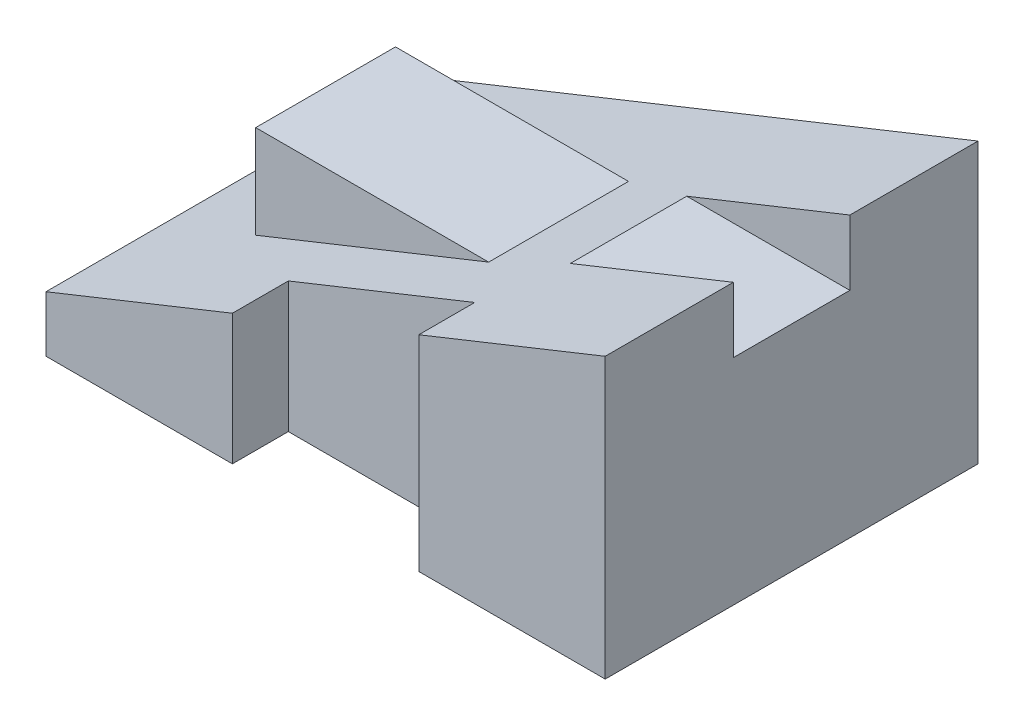
SolidWorks part; units mm, degrees
material "Plain Carbon Steel"
ref_plane "Front Plane" through (0, 0, 0) normal (0, 0, 1) x (1, 0, 0)
ref_plane "Top Plane" through (0, 0, 0) normal (0, 1, 0) x (1, 0, 0)
ref_plane "Right Plane" through (0, 0, 0) normal (1, 0, 0) x (0, 0, -1)
sketch "Sketch1" plane through (0, 0, 0) normal (0, 1, 0) x (1, 0, 0)
  line L0 (-20, -28) -> (-20, -40)
  line L1 (-60, 40) -> (60, 40)
  line L2 (-60, 40) -> (-60, -40)
  line L3 (-60, -40) -> (-20, -40)
  line L4 (60, 40) -> (60, -40)
  line L5 (-60, 40) -> (60, -40) construction
  line L6 (-60, -40) -> (60, 40) construction
  line L7 (-20, -28) -> (20, -28)
  line L9 (20, -28) -> (20, -40)
  line L12 (20, -40) -> (60, -40)
  point P0 (0, 0)
  point P6 (0, 0)
  point P7 (0, -40)
  point P8 (0, 0)
  point P11 (-20, -34)
  dimension "D1" = 60
  dimension "D2" = 40
  dimension "D3" = 40
  dimension "D4" = 40
  dimension "D5" = 28
extrude "Boss-Extrude1" add sketch "Sketch1" along normal blind 60
sketch "Sketch7" plane through (0, 0, 0) normal (0, 0, 1) x (1, 0, 0)
  line L0 (60, 60) -> (-60, 12)
  line L1 (-60, 60) -> (-60, 0) construction
  line L2 (-60, 12) -> (-60, 60)
  line L3 (-60, 60) -> (60, 60)
  dimension "D1" = 12
extrude "Cut-Extrude2" cut sketch "Sketch7" against normal mid plane 80
sketch "Sketch8" plane through (0, 0, 0) normal (0, 1, 0) x (1, 0, 0)
  line L0 (-60, 40) -> (-60, -40) construction
  line L1 (-40, 15) -> (60, 15)
  line L2 (-40, 15) -> (-40, -15)
  line L3 (-40, -15) -> (60, -15)
  line L4 (60, 15) -> (60, -15)
  dimension "D1" = 20
  dimension "D2" = 30
  dimension "D3" = 15
  dimension "D4" = 60
extrude "Boss-Extrude2" add sketch "Sketch8" along normal blind 40
sketch "Sketch9" plane through (0, 0, 0) normal (1, 0, 0) x (0, 0, -1)
  line L0 (-40, 44) -> (-40, 60) construction
  line L1 (12.5, 60) -> (-12.5, 60)
  line L2 (12.5, 60) -> (12.5, 46)
  line L3 (12.5, 46) -> (-12.5, 46)
  line L4 (-12.5, 60) -> (-12.5, 46)
  line L5 (12.5, 60) -> (-12.5, 46) construction
  line L6 (12.5, 46) -> (-12.5, 60) construction
  line L7 (-40, 60) -> (40, 60) construction
  point P0 (0, 53)
  dimension "D1" = 40
  dimension "D2" = 7
  dimension "D3" = 14
  dimension "D4" = 25
extrude "Cut-Extrude3" cut sketch "Sketch9" along normal through all
